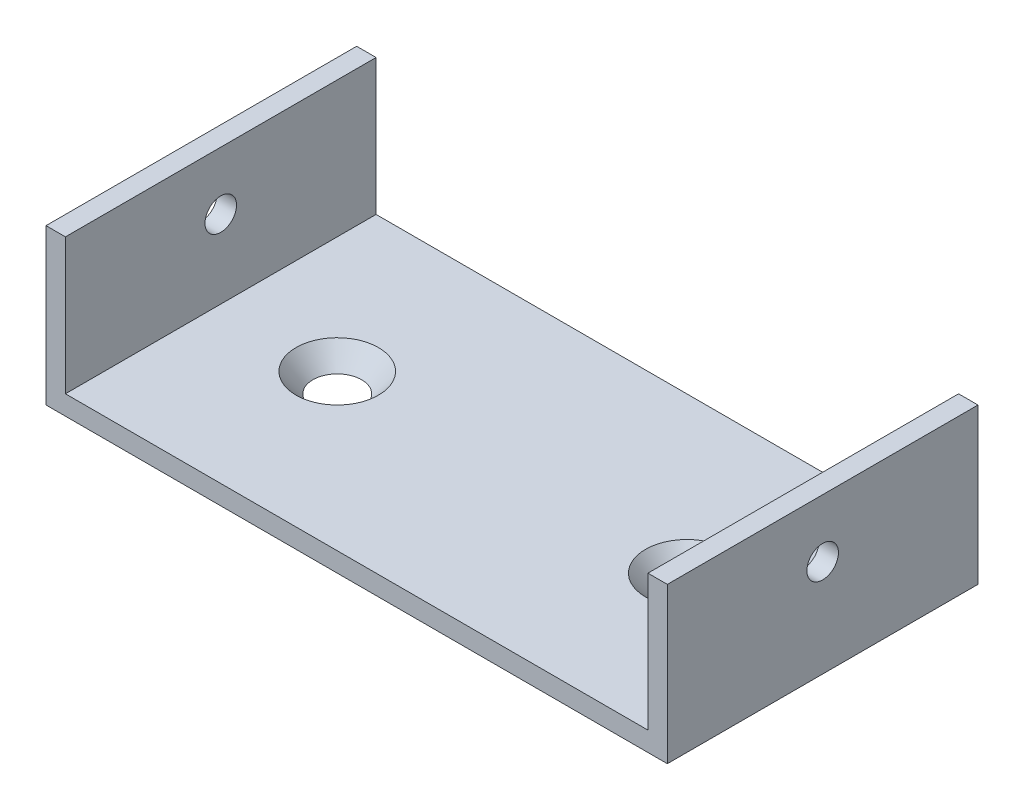
SolidWorks part; units mm, degrees
ref_plane "Front" through (0, 0, 0) normal (0, 0, 1) x (1, 0, 0)
ref_plane "Top" through (0, 0, 0) normal (0, 1, 0) x (1, 0, 0)
ref_plane "Right" through (0, 0, 0) normal (1, 0, 0) x (0, 0, -1)
sketch "Sketch1" plane through (0, 0, 0) normal (0, 0, 1) x (1, 0, 0)
  line L0 (0, -12.7) -> (0, 12.7) construction
  line L1 (-50.8, 0) -> (50.8, 0) construction
  line L2 (47.625, 12.7) -> (-47.625, 12.7) construction
  line L3 (-50.8, -12.7) -> (50.8, -12.7)
  line L4 (-50.8, -12.7) -> (-50.8, 12.7)
  line L5 (-50.8, 12.7) -> (50.8, 12.7)
  line L6 (50.8, -12.7) -> (50.8, 12.7)
  line L7 (-50.8, -12.7) -> (50.8, 12.7) construction
  line L8 (-50.8, 12.7) -> (50.8, -12.7) construction
  line L9 (-47.625, -12.7) -> (47.625, -12.7)
  point P3 (0, 0)
  point P4 (0, 0)
  point P8 (0, 0)
  point P13 (50.8, -9.525)
  point P17 (0, 12.7)
  point P20 (0, -12.7)
  dimension "Outside Width" = 101.6
  dimension "Outside Height" = 25.4
  dimension "Inside Height" = 22.225
  dimension "Wall Thickness" = 3.175
  dimension "Inside Width" = 95.25
sketch "Sketch2" plane through (0, 0, 0) normal (1, 0, 0) x (0, 0, -1)
  line L0 (-25.4, 0) -> (25.4, 0) construction
  dimension "Length" = 50.8
sketch "Sketch3" plane through (0, 0, 0) normal (0, 0, 1) x (1, 0, 0)
  line L0 (-50.8, 12.7) -> (-50.8, -12.7)
  line L1 (-50.8, -12.7) -> (50.8, -12.7)
  line L2 (50.8, -12.7) -> (50.8, 12.7)
  line L3 (50.8, 12.7) -> (47.625, 12.7)
  line L4 (47.625, 12.7) -> (47.625, -9.525)
  line L5 (47.625, -9.525) -> (-47.625, -9.525)
  line L6 (-47.625, -9.525) -> (-47.625, 12.7)
  line L7 (-47.625, 12.7) -> (-50.8, 12.7)
  line L8 (-47.625, -9.525) -> (-47.625, -12.7) construction
  dimension "D1" = 25.4
  dimension "D2" = 101.6
  dimension "D3" = 3.175
extrude "Boss-Extrude2" add sketch "Sketch3" along normal mid plane 50.8
sketch "Reference Sketch1" plane through (0, 0, 0) normal (1, 0, 0) x (0, 0, -1)
  line L0 (-25.4, 0) -> (25.4, 0) construction
  point P0 (19.05, 0)
  point P1 (-19.05, 0)
  dimension "D1" = 44.45
  dimension "D2" = 44.45
sketch "Sketch4" plane through (0, -9.525, 0) normal (0, 1, 0) x (1, 0, 0)
  line L0 (-47.625, 0) -> (-28.575, 0)
  line L1 (-47.625, -25.4) -> (-47.625, 25.4) construction
  line L2 (47.625, 0) -> (28.575, 0)
  line L3 (47.625, -25.4) -> (47.625, 25.4) construction
hole_wizard "1/4 (0.25) Diameter Hole1" positions "Sketch5" profile "Sketch6" hole size "1/4" standard "ANSI Inch" end condition through all
sketch "Sketch5" plane through (0, -9.525, 0) normal (0, 1, 0) x (1, 0, 0)
  point P0 (-28.575, 0)
  point P3 (28.575, 0)
sketch "Sketch6" plane through (-28.575, -9.525, 0) normal (1, 0, 0) x (0, 0, 1)
  line L0 (0, 0) -> (0, 3.175)
  line L1 (0, 3.175) -> (3.175, 3.175)
  line L2 (3.175, 3.175) -> (3.175, 4.1053)
  line L3 (3.175, 4.1053) -> (6.7437, 0)
  line L5 (6.7437, 0) -> (0, 0)
  line L6 (-3.175, 4.1053) -> (-6.7437, 0) construction
  line L11 (0, -6.35) -> (0, 107.95) construction
  dimension "Thru Hole Dia." = 6.35
  dimension "Thru Hole Depth" = 3.175
  dimension "Near C'Sink Dia." = 13.4874
  dimension "Near C'Sink Angle" = 82
sketch "Sketch7" plane through (50.8, 0, 0) normal (1, 0, 0) x (0, 0, -1)
  line L0 (0, -9.4842) -> (0, 3.2158)
hole_wizard "13/64 (0.20313) Diameter Hole1" positions "Sketch8" profile "Sketch9" hole size "13/64" standard "ANSI Inch" end condition through all
sketch "Sketch8" plane through (50.8, 0, 0) normal (1, 0, 0) x (0, 0, -1)
  point P0 (0, 3.2158)
sketch "Sketch9" plane through (50.8, 3.2158, 0) normal (0, 1, 0) x (0, 0, -1)
  line L0 (0, 0) -> (0, 101.6)
  line L1 (0, 101.6) -> (2.5798, 101.6)
  line L2 (2.5798, 101.6) -> (2.5798, 0)
  line L5 (2.5798, 0) -> (0, 0)
  line L11 (0, -6.35) -> (0, 107.95) construction
  dimension "Thru Hole Dia." = 5.1595
  dimension "Thru Hole Depth" = 101.6
equation "\"D1@Sketch3\" = \"Outside Height@Sketch1\""
equation "\"D2@Sketch3\" = \"Outside Width@Sketch1\""
equation "\"D3@Sketch3\" = \"Wall Thickness@Sketch1\""
equation "\"D1@Reference Sketch1\"=\"Outside Height@Sketch1\" * 1.75"
equation "\"D2@Reference Sketch1\" = \"D1@Reference Sketch1\""
equation "\"D1@Boss-Extrude2\" = \"Length@Sketch2\""
equation "\"Inside Height@Sketch1\"=\"Outside Height@Sketch1\"-\"Wall Thickness@Sketch1\""
equation "\"Inside Width@Sketch1\"=\"Outside Width@Sketch1\"-\"Wall Thickness@Sketch1\"*2"
